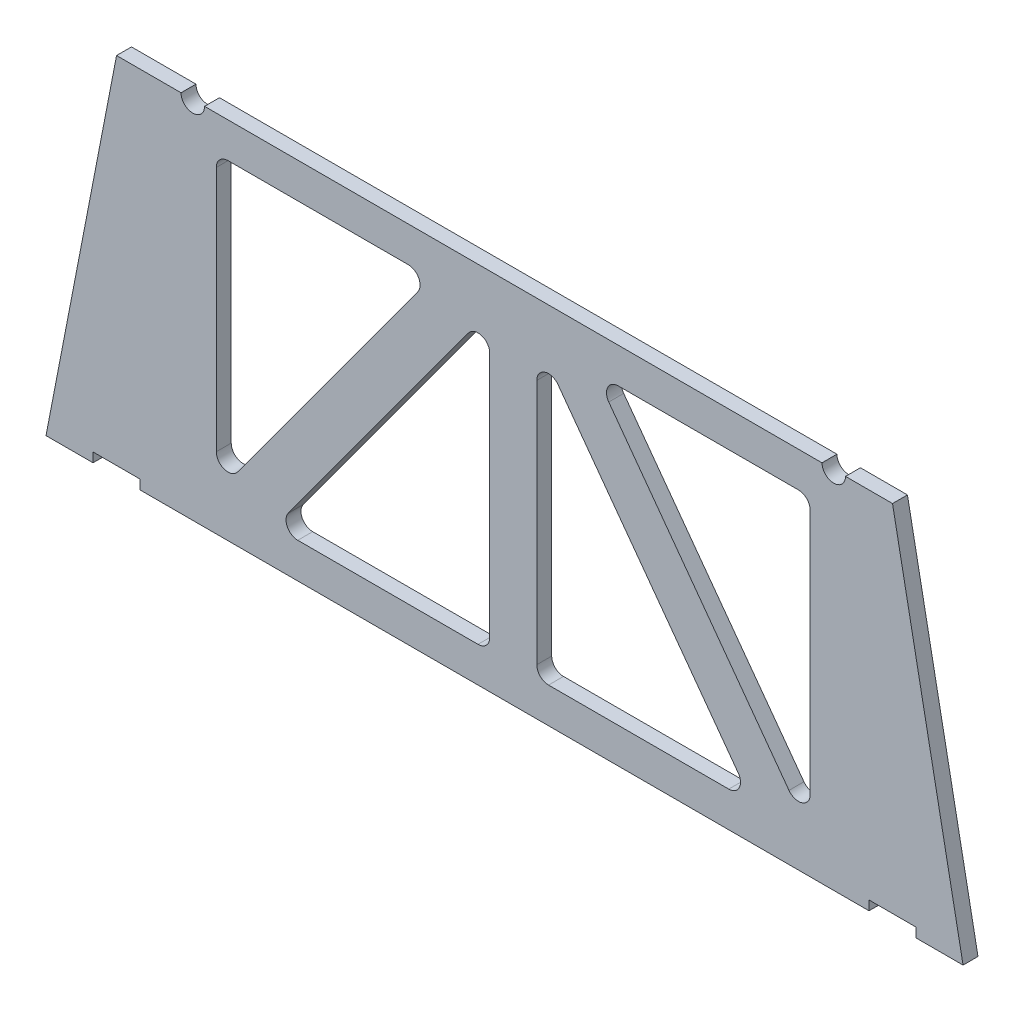
SolidWorks part; units mm, degrees
ref_plane "Front Plane" through (0, 0, 0) normal (0, 0, 1) x (1, 0, 0)
ref_plane "Top Plane" through (0, 0, 0) normal (0, 1, 0) x (1, 0, 0)
ref_plane "Right Plane" through (0, 0, 0) normal (1, 0, 0) x (0, 0, -1)
sketch "Sketch1" plane through (0, 0, 0) normal (0, 0, 1) x (1, 0, 0)
  line L0 (-158.7125, -77.5) -> (151.2875, -77.5)
  line L1 (191.2875, -77.5) -> (161.2875, 77.5)
  line L2 (161.2875, 77.5) -> (141.2875, 77.5)
  line L3 (-168.7125, 77.5) -> (-198.7125, -77.5)
  line L4 (-198.7125, -77.5) -> (-178.7125, -77.5)
  line L5 (-178.7125, -77.5) -> (-178.7125, -73.5)
  line L6 (-178.7125, -73.5) -> (-158.7125, -73.5)
  line L7 (-158.7125, -73.5) -> (-158.7125, -77.5)
  line L8 (-168.7125, 77.5) -> (-141.2875, 77.5)
  line L9 (151.2875, -77.5) -> (151.2875, -73.5)
  line L10 (151.2875, -73.5) -> (171.2875, -73.5)
  line L11 (171.2875, -73.5) -> (171.2875, -77.5)
  line L12 (171.2875, -77.5) -> (191.2875, -77.5)
  line L13 (-168.7125, 77.5) -> (-141.2875, 77.5)
  line L14 (0, -77.5) -> (0, 77.5) construction
  line L15 (-131.2875, 77.5) -> (131.2875, 77.5)
  line L16 (-126.2875, 57.5) -> (-126.2875, -47.2046)
  line L17 (-117.2529, -50.1579) -> (-40.6078, 54.5466)
  line L18 (-121.2875, 62.5) -> (-44.6424, 62.5)
  line L19 (-95.6797, -54.5466) -> (-19.0346, 50.1579)
  line L20 (-10, 47.2046) -> (-10, -57.5)
  line L21 (-91.6451, -62.5) -> (-15, -62.5)
  line L22 (15, -62.5) -> (91.6451, -62.5)
  line L23 (10, 47.2046) -> (10, -57.5)
  line L24 (95.6797, -54.5466) -> (19.0346, 50.1579)
  line L25 (44.6424, 62.5) -> (121.2875, 62.5)
  line L26 (117.2529, -50.1579) -> (40.6078, 54.5466)
  line L27 (126.2875, 57.5) -> (126.2875, -47.2046)
  arc A0 (-141.2875, 77.5) -> (-131.2875, 77.5) centre (-136.2875, 77.5) ccw
  arc A1 (141.2875, 77.5) -> (131.2875, 77.5) centre (136.2875, 77.5) cw
  arc A2 (-126.2875, 57.5) -> (-121.2875, 62.5) centre (-121.2875, 57.5) cw
  arc A3 (-117.2529, -50.1579) -> (-126.2875, -47.2046) centre (-121.2875, -47.2046) cw
  arc A4 (-40.6078, 54.5466) -> (-44.6424, 62.5) centre (-44.6424, 57.5) ccw
  arc A5 (-10, 47.2046) -> (-19.0346, 50.1579) centre (-15, 47.2046) ccw
  arc A6 (-15, -62.5) -> (-10, -57.5) centre (-15, -57.5) ccw
  arc A7 (-91.6451, -62.5) -> (-95.6797, -54.5466) centre (-91.6451, -57.5) cw
  arc A8 (10, 47.2046) -> (19.0346, 50.1579) centre (15, 47.2046) cw
  arc A9 (10, -57.5) -> (15, -62.5) centre (15, -57.5) ccw
  arc A10 (91.6451, -62.5) -> (95.6797, -54.5466) centre (91.6451, -57.5) ccw
  arc A11 (44.6424, 62.5) -> (40.6078, 54.5466) centre (44.6424, 57.5) ccw
  arc A12 (126.2875, 57.5) -> (121.2875, 62.5) centre (121.2875, 57.5) ccw
  arc A13 (117.2529, -50.1579) -> (126.2875, -47.2046) centre (121.2875, -47.2046) ccw
  point P15 (0, -77.5)
  point P29 (0, 0)
  point P37 (-126.2875, 62.5)
  point P40 (-126.2875, -62.5)
  point P43 (-34.7858, 62.5)
  point P46 (-10, 62.5)
  point P49 (-10, -62.5)
  point P52 (-101.5017, -62.5)
  point P55 (10, 62.5)
  point P58 (10, -62.5)
  point P61 (101.5017, -62.5)
  point P64 (34.7858, 62.5)
  point P67 (126.2875, 62.5)
  point P70 (126.2875, -62.5)
  dimension "D18" = 5
  dimension "D1" = 20
  dimension "D2" = 20
  dimension "D3" = 20
  dimension "D4" = 282.575
  dimension "D5" = 15
  dimension "D6" = 10
  dimension "D7" = 20
  dimension "D8" = 4
  dimension "D9" = 10
  dimension "D10" = 310
  dimension "D11" = 5
  dimension "D13" = 20
  dimension "D14" = 10
  dimension "D15" = 15
  dimension "D16" = 155
  dimension "D17" = 5
extrude "Extrude1" add sketch "Sketch1" along normal blind 6.35 contours L0 L14 L15 A0 L8 L3 L4 L5 L6 L7 L16 L18 L17 L21 L19 L20 | L14 L0 L9 L10 L11 L12 L1 L2 A1 L15 L25 L27 L26 L24 L22 L23
